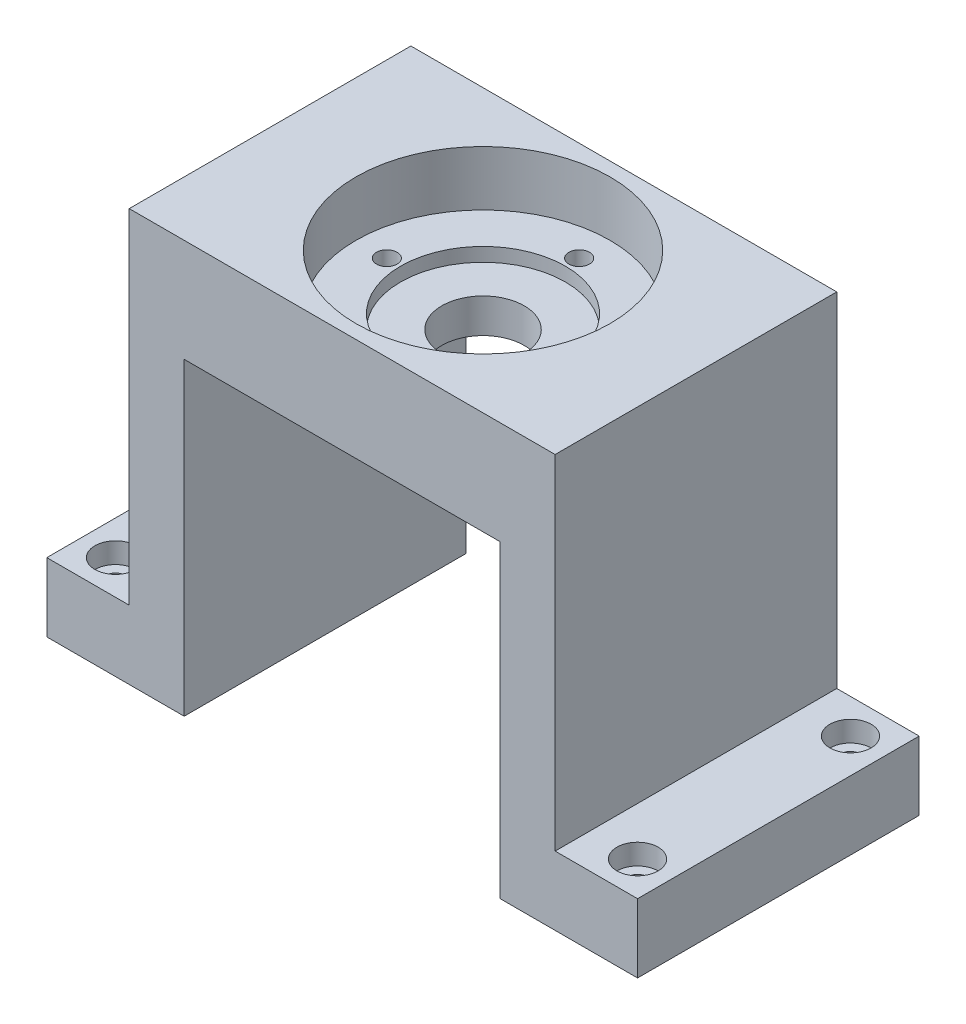
SolidWorks part; units mm, degrees
ref_plane "Front Plane" through (0, 0, 0) normal (0, 0, 1) x (1, 0, 0)
ref_plane "Top Plane" through (0, 0, 0) normal (0, 1, 0) x (1, 0, 0)
ref_plane "Right Plane" through (0, 0, 0) normal (1, 0, 0) x (0, 0, -1)
sketch "Sketch1" plane through (0, 0, 0) normal (0, 1, 0) x (1, 0, 0)
  line L0 (0, 97.8862) -> (0, -94.0143) construction
  line L1 (43, 20.5) -> (43, -20.5)
  line L6 (-43, 20.5) -> (-23, 20.5)
  line L7 (-43, 20.5) -> (-43, -20.5)
  line L8 (-43, -20.5) -> (-23, -20.5)
  line L9 (-23, 20.5) -> (-23, -20.5)
  line L10 (-43, 20.5) -> (-23, -20.5) construction
  line L11 (-43, -20.5) -> (-23, 20.5) construction
  line L12 (43, 20.5) -> (23, -20.5) construction
  line L13 (43, -20.5) -> (23, 20.5) construction
  line L14 (43, 20.5) -> (23, 20.5)
  line L15 (23, 20.5) -> (23, -20.5)
  line L16 (43, -20.5) -> (23, -20.5)
  point P3 (-33, 0)
  point P4 (0, 0)
  point P14 (33, 0)
  dimension "D1" = 23
  dimension "D2" = 20
  dimension "D3" = 41
extrude "Boss-Extrude1" add sketch "Sketch1" along normal blind 10
sketch "Sketch2" plane through (0, 10, 0) normal (0, 1, 0) x (1, 0, 0)
  line L0 (0, 35.1672) -> (0, -39.123) construction
  line L1 (-23, 20.5) -> (-43, 20.5) construction
  line L2 (-43, 20.5) -> (-43, -20.5) construction
  line L3 (-43, -20.5) -> (-23, -20.5) construction
  circle A0 centre (-38, 15.5) radius 1.5
  circle A1 centre (-38, -15.5) radius 1.5
  circle A2 centre (38, -15.5) radius 1.5
  circle A3 centre (38, 15.5) radius 1.5
  dimension "D1" = 3
  dimension "D2" = 3
  dimension "D3" = 5
  dimension "D5" = 5
  dimension "D6" = 5
  dimension "D4" = 5
extrude "Cut-Extrude1" cut sketch "Sketch2" against normal up to next (10 mm away)
sketch "Sketch3" plane through (0, 10, 0) normal (0, 1, 0) x (1, 0, 0)
  circle A0 centre (-38, 15.5) radius 3
  circle A1 centre (-38, -15.5) radius 3
  circle A2 centre (38, -15.5) radius 3
  circle A3 centre (38, 15.5) radius 3
  dimension "D1" = 6
  dimension "D2" = 6
  dimension "D3" = 6
  dimension "D4" = 6
extrude "Cut-Extrude2" cut sketch "Sketch3" against normal blind 3
sketch "Sketch4" plane through (0, 10, 0) normal (0, 1, 0) x (1, 0, 0)
  line L0 (0, 31.3083) -> (0, -26.8809) construction
  line L1 (-43, -20.5) -> (-23, -20.5) construction
  line L2 (-23, 20.5) -> (-31, 20.5)
  line L3 (-23, 20.5) -> (-23, -20.5)
  line L4 (-23, -20.5) -> (-31, -20.5)
  line L5 (-31, 20.5) -> (-31, -20.5)
  line L6 (23, 20.5) -> (23, -20.5)
  line L7 (23, 20.5) -> (31, 20.5)
  line L8 (31, 20.5) -> (31, -20.5)
  line L9 (23, -20.5) -> (31, -20.5)
  dimension "D1" = 8
extrude "Boss-Extrude2" add sketch "Sketch4" along normal blind 35
sketch "Sketch5" plane through (0, 45, 0) normal (0, 1, 0) x (1, 0, 0)
  line L1 (-31, 20.5) -> (31, 20.5)
  line L2 (-31, 20.5) -> (-31, -20.5)
  line L3 (-31, -20.5) -> (31, -20.5)
  line L4 (31, 20.5) -> (31, -20.5)
extrude "Boss-Extrude3" add sketch "Sketch5" along normal blind 15
sketch "Sketch6" plane through (0, 60, 0) normal (0, 1, 0) x (1, 0, 0)
  circle A0 centre (0, 0) radius 18 construction
  circle A1 centre (0, 0) radius 14 construction
  circle A2 centre (-14, 0) radius 1.5
  circle A3 centre (0, 14) radius 1.5
  circle A4 centre (14, 0) radius 1.5
  circle A5 centre (0, -14) radius 1.5
  dimension "D1" = 36
  dimension "D2" = 28
  dimension "D3" = 3
  dimension "D4" = 3
  dimension "D5" = 3
  dimension "D6" = 3
extrude "Cut-Extrude3" cut sketch "Sketch6" against normal up to next
sketch "Sketch7" plane through (0, 45, 0) normal (0, -1, 0) x (1, 0, 0)
  circle A0 centre (0, 14) radius 3
  circle A1 centre (14, 0) radius 3
  circle A2 centre (0, -14) radius 3
  circle A3 centre (-14, 0) radius 3
  dimension "D1" = 6
  dimension "D2" = 6
  dimension "D3" = 6
  dimension "D4" = 6
extrude "Cut-Extrude4" cut sketch "Sketch7" against normal blind 3
sketch "Sketch8" plane through (0, 60, 0) normal (0, 1, 0) x (1, 0, 0)
  circle A0 centre (0, 0) radius 12
  dimension "D1" = 24
extrude "Cut-Extrude5" cut sketch "Sketch8" against normal blind 10
sketch "Sketch9" plane through (0, 60, 0) normal (0, 1, 0) x (1, 0, 0)
  circle A0 centre (0, 0) radius 6
  dimension "D1" = 12
extrude "Cut-Extrude6" cut sketch "Sketch9" against normal up to next and the other way through all
sketch "Sketch10" plane through (0, 60, 0) normal (0, 1, 0) x (1, 0, 0)
  circle A0 centre (0, 0) radius 18.5
  dimension "D1" = 37
extrude "Cut-Extrude7" cut sketch "Sketch10" against normal blind 8
equation "\"D1@Sketch1\"=36/2+5"
